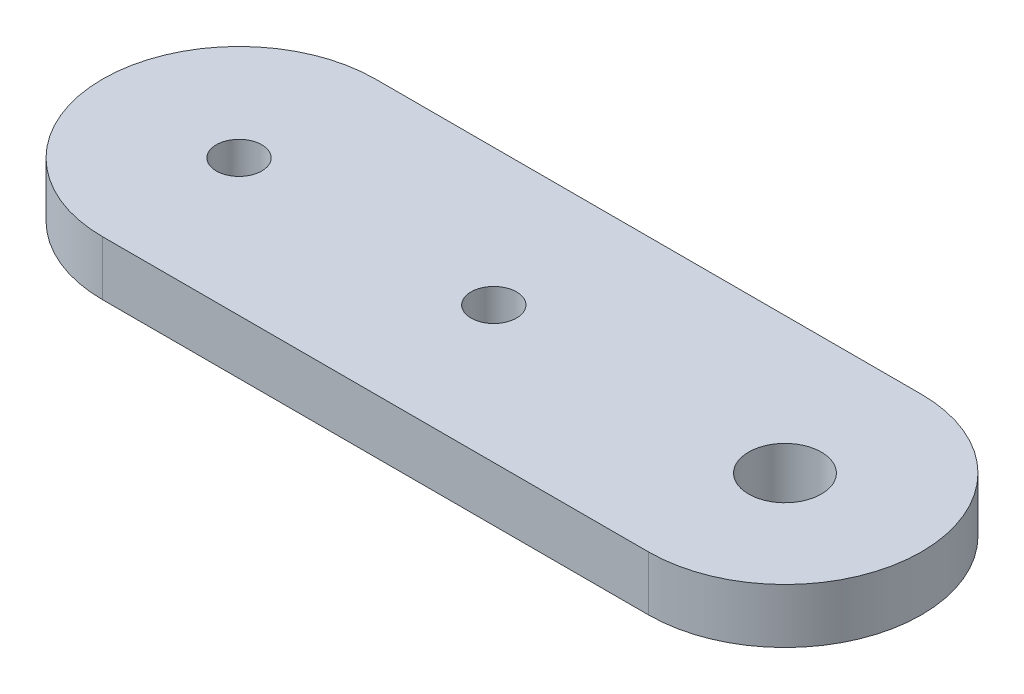
SolidWorks part; units mm, degrees
ref_plane "Front Plane" through (0, 0, 0) normal (0, 0, 1) x (1, 0, 0)
ref_plane "Top Plane" through (0, 0, 0) normal (0, 1, 0) x (1, 0, 0)
ref_plane "Right Plane" through (0, 0, 0) normal (1, 0, 0) x (0, 0, -1)
sketch "Sketch1" plane through (0, 0, 0) normal (0, 1, 0) x (1, 0, 0)
  line L0 (0, 0) -> (30, 0) construction
  line L1 (0, 7.5) -> (30, 7.5)
  line L2 (0, -7.5) -> (30, -7.5)
  arc A0 (0, 7.5) -> (0, -7.5) centre (0, 0) ccw
  arc A1 (30, -7.5) -> (30, 7.5) centre (30, 0) ccw
  circle A2 centre (30, 0) radius 2
  circle A3 centre (0, 0) radius 1.25
  circle A4 centre (14, 0) radius 1.25
  point P3 (15, 0)
  dimension "D2" = 4
  dimension "D3" = 7.5
  dimension "D4" = 2.5
  dimension "D5" = 2.5
  dimension "D1" = 30
  dimension "D6" = 14
extrude "Boss-Extrude1" add sketch "Sketch1" along normal blind 3
